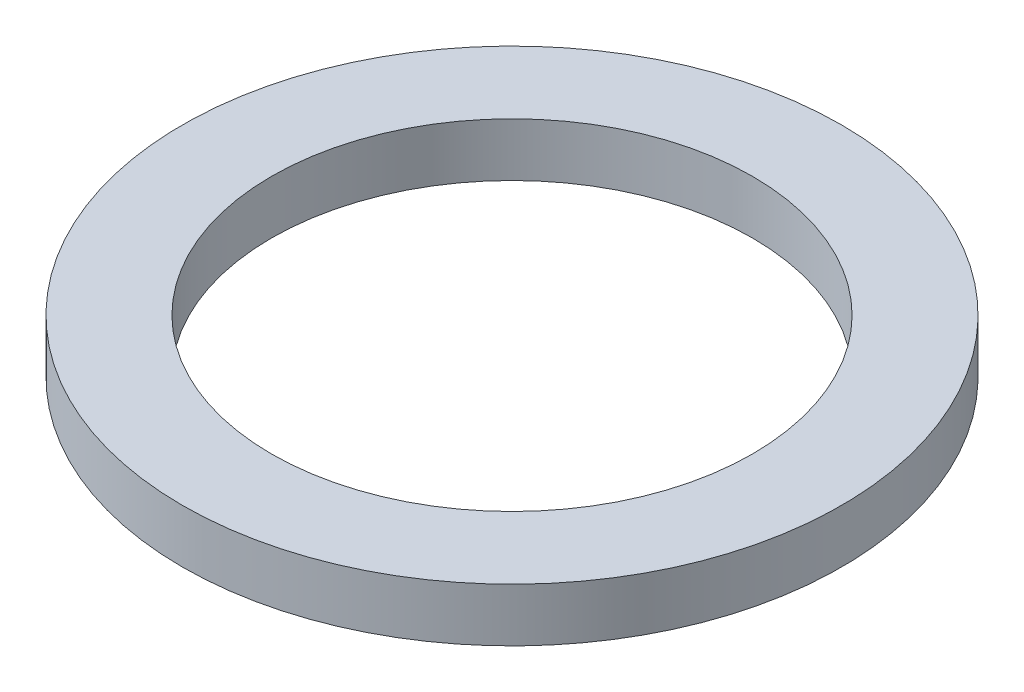
SolidWorks part; units mm, degrees
material "Teak"
ref_plane "Front Plane" through (0, 0, 0) normal (0, 0, 1) x (1, 0, 0)
ref_plane "Top Plane" through (0, 0, 0) normal (0, 1, 0) x (1, 0, 0)
ref_plane "Right Plane" through (0, 0, 0) normal (1, 0, 0) x (0, 0, -1)
sketch "Sketch2" plane through (0, 0, 0) normal (0, 1, 0) x (1, 0, 0)
  circle A0 centre (0, 0) radius 13.5
  circle A1 centre (0, 0) radius 18.5
  dimension "D1" = 27
  dimension "D2" = 37
extrude "Boss-Extrude1" add sketch "Sketch2" along normal blind 3
